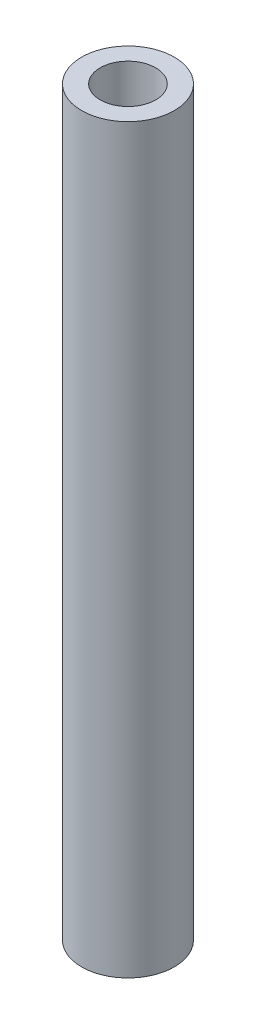
SolidWorks part; units mm, degrees
ref_plane "Спереди" through (0, 0, 0) normal (0, 0, 1) x (1, 0, 0)
ref_plane "Сверху" through (0, 0, 0) normal (0, 1, 0) x (1, 0, 0)
ref_plane "Справа" through (0, 0, 0) normal (1, 0, 0) x (0, 0, -1)
sketch "Эскиз8" plane through (0, 0, 0) normal (0, 1, 0) x (1, 0, 0)
  circle A0 centre (0, 0) radius 5
  dimension "D1" = 10
extrude "Бобышка-Вытянуть2" add sketch "Эскиз8" along normal blind 80
sketch "Эскиз9" plane through (0, 80, 0) normal (0, 1, 0) x (1, 0, 0)
  circle A0 centre (0, 0) radius 3
  dimension "D1" = 6
extrude "Вырез-Вытянуть5" cut sketch "Эскиз9" against normal blind 75
sketch "Эскиз12" plane through (0, 0, 0) normal (0, -1, 0) x (1, 0, 0)
  circle A0 centre (0, 0) radius 1.55
  dimension "D1" = 3.1
extrude "Вырез-Вытянуть7" cut sketch "Эскиз12" against normal blind 5
